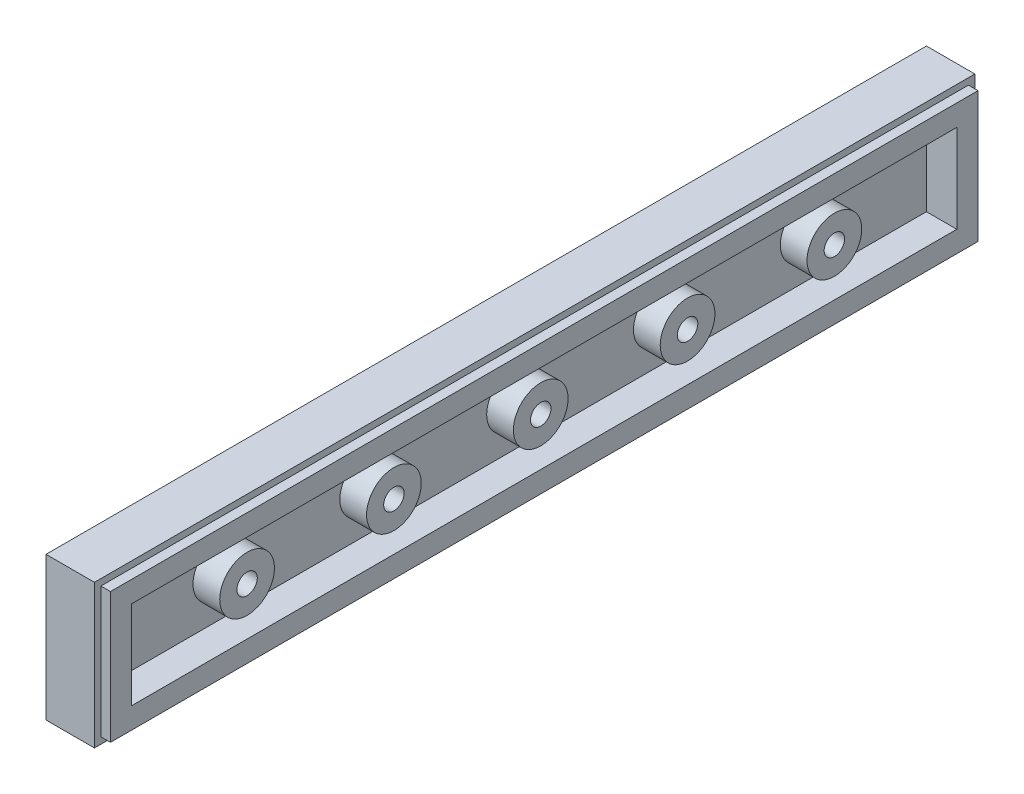
SolidWorks part; units mm, degrees
ref_plane "Front Plane" through (0, 0, 0) normal (0, 0, 1) x (1, 0, 0)
ref_plane "Top Plane" through (0, 0, 0) normal (0, 1, 0) x (1, 0, 0)
ref_plane "Right Plane" through (0, 0, 0) normal (1, 0, 0) x (0, 0, -1)
sketch "Sketch1" plane through (0, 0, 0) normal (1, 0, 0) x (0, 0, -1)
  line L1 (-23.895, 3.895) -> (23.895, 3.895)
  line L2 (-23.895, 3.895) -> (-23.895, -3.895)
  line L3 (-23.895, -3.895) -> (23.895, -3.895)
  line L4 (23.895, 3.895) -> (23.895, -3.895)
  line L5 (-23.895, 3.895) -> (23.895, -3.895) construction
  line L6 (-23.895, -3.895) -> (23.895, 3.895) construction
  point P0 (0, 0)
  dimension "D1" = 7.79
  dimension "D2" = 47.79
extrude "Boss-Extrude1" add sketch "Sketch1" along normal blind 2.63
shell "Shell1" thickness 1.5
sketch "Sketch2" plane through (2.63, 0, 0) normal (1, 0, 0) x (0, 0, -1)
  line L0 (-23.545, 3.545) -> (23.545, 3.545)
  line L1 (23.545, 3.545) -> (23.545, -3.545)
  line L2 (23.545, -3.545) -> (-23.545, -3.545)
  line L3 (-23.545, -3.545) -> (-23.545, 3.545)
  line L4 (-22.395, 2.395) -> (-22.395, -2.395)
  line L5 (-22.395, -2.395) -> (22.395, -2.395)
  line L6 (22.395, -2.395) -> (22.395, 2.395)
  line L7 (22.395, 2.395) -> (-22.395, 2.395)
  dimension "D1" = 1.15
  dimension "D2" = 1.15
  dimension "D3" = 1.15
  dimension "D4" = 1.15
extrude "Boss-Extrude2" add sketch "Sketch2" along normal blind 0.52
sketch "Sketch3" plane through (1.5, 0, 0) normal (1, 0, 0) x (0, 0, -1)
  line L0 (23.895, 3.895) -> (-23.895, 3.895) construction
  line L2 (-23.895, 3.895) -> (-23.895, -3.895) construction
  circle A0 centre (-15.93, 0) radius 1.485
  circle A1 centre (-15.93, 0) radius 0.555
  circle A2 centre (-7.96, 0) radius 0.555
  circle A3 centre (-7.96, 0) radius 1.485
  circle A4 centre (0.01, 0) radius 0.555
  circle A5 centre (0.01, 0) radius 1.485
  circle A6 centre (7.98, 0) radius 0.555
  circle A7 centre (7.98, 0) radius 1.485
  circle A8 centre (15.95, 0) radius 0.555
  circle A9 centre (15.95, 0) radius 1.485
  dimension "D2" = 7.965
  dimension "D4" = 2.97
  dimension "D5" = 1.11
  dimension "D6" = 7.97
  dimension "D1" = 3.895
  dimension "D3" = 5
extrude "Boss-Extrude3" add sketch "Sketch3" along normal offset from surface (1.45 mm away) 0.2 up to face at (3.15, 0, 0)
